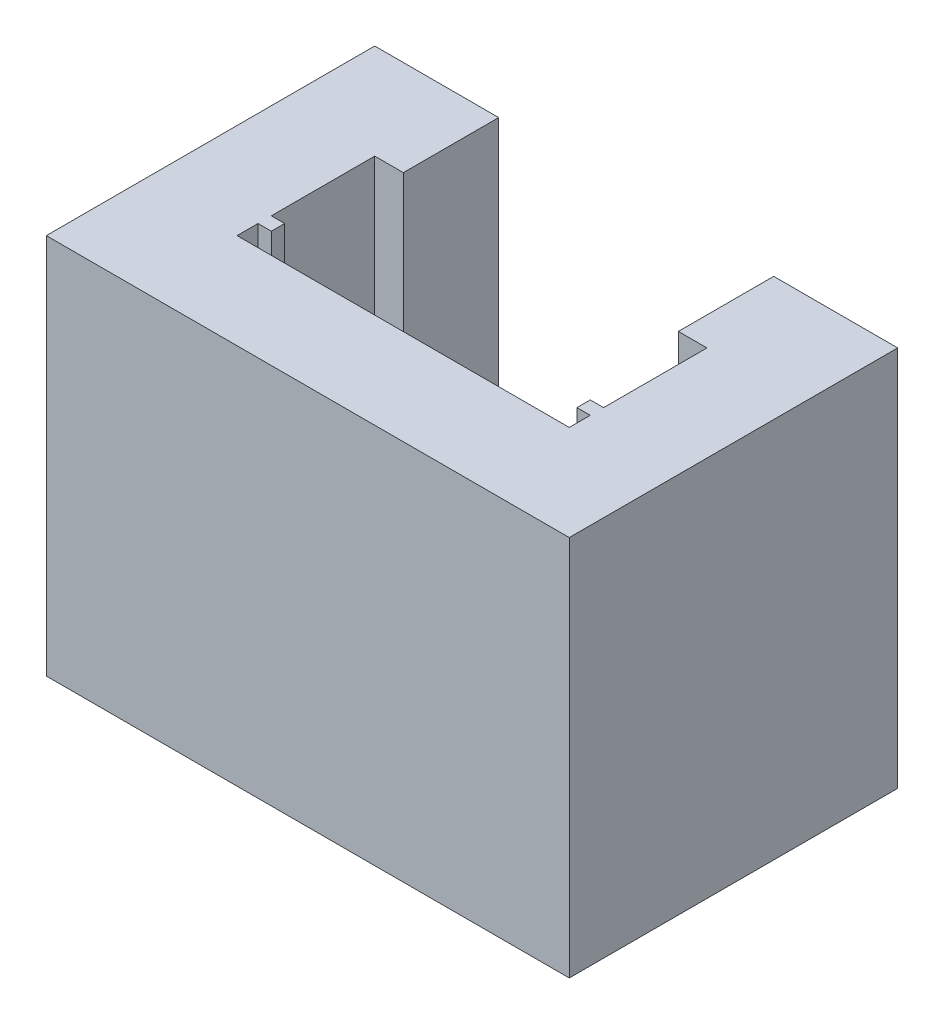
SolidWorks part; units mm, degrees
ref_plane "Front Plane" through (0, 0, 0) normal (0, 0, 1) x (1, 0, 0)
ref_plane "Top Plane" through (0, 0, 0) normal (0, 1, 0) x (1, 0, 0)
ref_plane "Right Plane" through (0, 0, 0) normal (1, 0, 0) x (0, 0, -1)
sketch "Sketch1" plane through (0, 0, 0) normal (0, 1, 0) x (1, 0, 0)
  line L0 (-8.71, 0) -> (8.71, 0)
  line L1 (8.71, 0) -> (8.71, 1.1)
  line L2 (8.71, 7.22) -> (7.21, 7.22)
  line L3 (0, 0) -> (0, 19.6218) construction
  line L4 (-8.71, 7.22) -> (-7.21, 7.22)
  line L5 (-8.71, 0) -> (-8.71, 1.1)
  line L6 (-13.71, 12.22) -> (-7.21, 12.22)
  line L7 (-13.71, -5) -> (-13.71, 12.22)
  line L8 (-13.71, -5) -> (13.71, -5)
  line L9 (13.71, -5) -> (13.71, 12.22)
  line L10 (13.71, 12.22) -> (7.21, 12.22)
  line L11 (-7.21, 7.22) -> (-7.21, 12.22)
  line L12 (7.21, 12.22) -> (7.21, 7.22)
  line L13 (-8.71, 1.8) -> (-8.71, 7.22)
  line L14 (-8.71, 1.1) -> (-8.01, 1.1)
  line L15 (-8.01, 1.1) -> (-8.01, 1.8)
  line L16 (-8.01, 1.8) -> (-8.71, 1.8)
  line L18 (-8.71, 0) -> (-8.71, 7.22) construction
  line L19 (8.01, 1.8) -> (8.71, 1.8)
  line L20 (8.01, 1.1) -> (8.01, 1.8)
  line L21 (8.71, 1.1) -> (8.01, 1.1)
  line L22 (8.71, 1.8) -> (8.71, 7.22)
  line L23 (8.71, 0) -> (8.71, 7.22) construction
  dimension "D1" = 8.71
  dimension "D2" = 7.22
  dimension "D3" = 5
  dimension "1.5" = 1.5
  dimension "D4" = 1.1
  dimension "D5" = 0.7
  dimension "D6" = 0.7
extrude "Boss-Extrude1" add sketch "Sketch1" along normal blind 20
